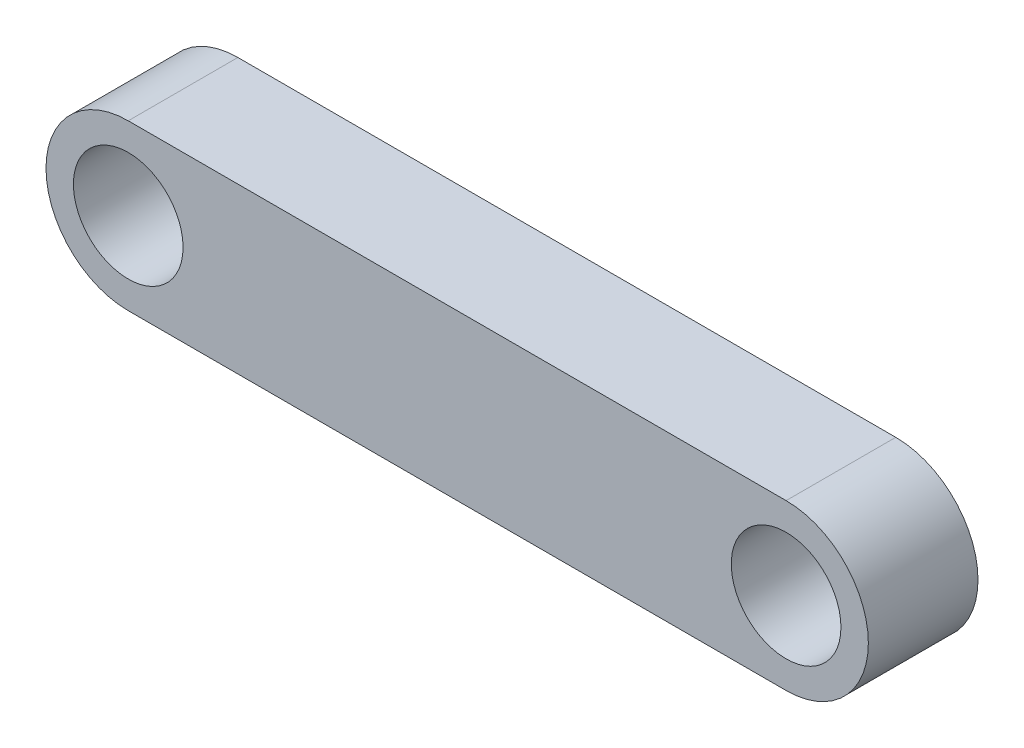
SolidWorks part; units mm, degrees
ref_plane "Alzado" through (0, 0, 0) normal (0, 0, 1) x (1, 0, 0)
ref_plane "Planta" through (0, 0, 0) normal (0, 1, 0) x (1, 0, 0)
ref_plane "Vista lateral" through (0, 0, 0) normal (1, 0, 0) x (0, 0, -1)
sketch "Croquis1" plane through (0, 0, 0) normal (0, 0, 1) x (1, 0, 0)
  line L0 (0, 0) -> (60, 0) construction
  line L2 (0, 7.5) -> (60, 7.5)
  line L3 (0, -7.5) -> (60, -7.5)
  arc A0 (0, 7.5) -> (0, -7.5) centre (0, 0) ccw
  arc A1 (60, -7.5) -> (60, 7.5) centre (60, 0) ccw
  circle A2 centre (0, 0) radius 5
  circle A3 centre (60, 0) radius 5
  point P5 (30, 0)
extrude "Saliente-Extruir1" add sketch "Croquis1" along normal blind 10
